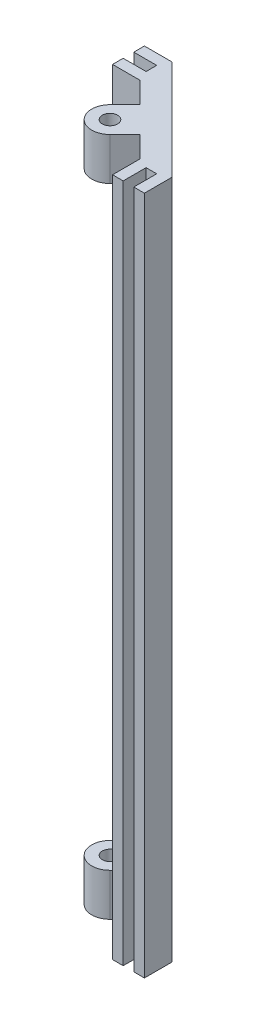
SolidWorks part; units mm, degrees
ref_plane "Front Plane" through (0, 0, 0) normal (0, 0, 1) x (1, 0, 0)
ref_plane "Top Plane" through (0, 0, 0) normal (0, 1, 0) x (1, 0, 0)
ref_plane "Right Plane" through (0, 0, 0) normal (1, 0, 0) x (0, 0, -1)
sketch "Sketch1" plane through (0, 0, 0) normal (0, 1, 0) x (1, 0, 0)
  line L0 (0, 0) -> (31.75, 0) construction
  line L1 (38.1, 0) -> (38.1, 25.4) construction
  line L2 (25.4, 38.1) -> (0, 38.1) construction
  line L3 (0, 38.1) -> (0, 34.925) construction
  line L4 (38.1, 0) -> (38.1, 8.2099)
  line L5 (38.1, 8.2099) -> (8.2099, 38.1)
  line L6 (8.2099, 38.1) -> (0, 38.1)
  line L7 (0, 38.1) -> (0, 34.925)
  line L8 (0, 28.575) -> (8.2099, 28.575)
  line L9 (8.2099, 28.575) -> (14.5309, 22.2539)
  line L10 (28.575, 8.2099) -> (28.575, 0)
  line L11 (28.575, 0) -> (31.75, 0)
  line L12 (34.3803, 34.3803) -> (23.1549, 23.1549) construction
  line L13 (0, 31.75) -> (0, 0) construction
  line L15 (31.75, 0) -> (31.75, 6.858)
  line L16 (31.75, 6.858) -> (34.925, 6.858)
  line L17 (34.925, 0) -> (34.925, 6.858)
  line L22 (0, 31.75) -> (6.858, 31.75)
  line L24 (0, 34.925) -> (6.858, 34.925)
  line L25 (6.858, 31.75) -> (6.858, 34.925)
  line L26 (0, 31.75) -> (0, 28.575)
  line L27 (34.925, 0) -> (38.1, 0) construction
  line L28 (34.925, 0) -> (38.1, 0)
  line L29 (14.5309, 22.2539) -> (10.0408, 17.7638)
  line L31 (17.7638, 10.0408) -> (22.2539, 14.5309)
  line L32 (22.2539, 14.5309) -> (28.575, 8.2099)
  arc A0 (10.0408, 17.7638) -> (17.7638, 10.0408) centre (13.9023, 13.9023) ccw
  circle A1 centre (13.9023, 13.9023) radius 2.286
  arc A2 (38.1, 25.4) -> (25.4, 38.1) centre (25.4, 25.4) ccw construction
  dimension "D4" = 4.572
  dimension "D9" = 3.175
  dimension "D12" = 6.7352
  dimension "D10" = 10.922
  dimension "D13" = 12.7
  dimension "D1" = 38.1
  dimension "D2" = 38.1
  dimension "D3" = 3.175
  dimension "D5" = 3.175
  dimension "D6" = 3.175
  dimension "D7" = 3.175
  dimension "D8" = 6.858
  dimension "D11" = 6.35
  dimension "D14" = 15.875
  dimension "D15" = 13.0852
  dimension "D16" = 28.9602
extrude "Boss-Extrude1" add sketch "Sketch1" along normal blind 203.2
sketch "Sketch2" plane through (18.3924, 0, -18.3924) normal (-0.7071, 0, 0.7071) x (0.7071, 0, 0.7071)
  line L0 (5.461, 203.2) -> (5.461, 0) construction
  line L1 (5.461, 12.7) -> (-5.461, 12.7)
  line L2 (5.461, 12.7) -> (5.461, 190.5)
  line L3 (5.461, 190.5) -> (-5.461, 190.5)
  line L4 (-5.461, 12.7) -> (-5.461, 190.5)
  line L5 (-5.461, 203.2) -> (-5.461, 0) construction
  line L6 (5.461, 203.2) -> (-5.461, 203.2) construction
  line L7 (-5.461, 0) -> (5.461, 0) construction
  dimension "D1" = 12.7
  dimension "D2" = 12.7
extrude "Cut-Extrude1" cut sketch "Sketch2" along normal up to vertex
sketch "Sketch3" plane through (18.3924, 0, -18.3924) normal (-0.7071, 0, 0.7071) x (0.7071, 0, 0.7071)
  line L1 (-5.461, 190.5) -> (5.461, 190.5) construction
  line L2 (-3.175, 190.5) -> (3.175, 190.5)
  line L3 (-3.175, 190.5) -> (-3.175, 12.7)
  line L4 (-3.175, 12.7) -> (3.175, 12.7)
  line L5 (3.175, 190.5) -> (3.175, 12.7)
  line L6 (-5.461, 12.7) -> (5.461, 12.7) construction
  point P0 (0, 12.7)
  dimension "D1" = 6.35
extrude "Boss-Extrude2" add sketch "Sketch3" along normal blind 1.27
